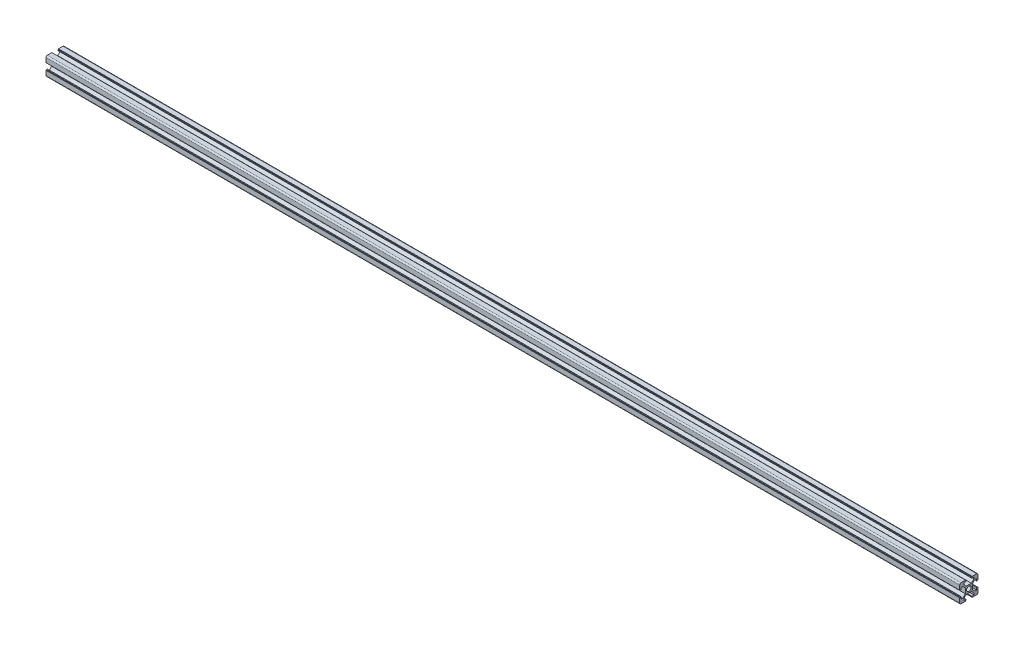
SolidWorks part; units mm, degrees
ref_plane "前视基准面" through (0, 0, 0) normal (0, 0, 1) x (1, 0, 0)
ref_plane "上视基准面" through (0, 0, 0) normal (0, 1, 0) x (1, 0, 0)
ref_plane "右视基准面" through (0, 0, 0) normal (1, 0, 0) x (0, 0, -1)
sketch "草图1" plane through (0, 0, 0) normal (0, 1, 0) x (1, 0, 0)
  line L0 (0, 0) -> (1000, 0)
  dimension "D1" = 1000
other "铝型材 20 X 20 X R1.5(1)"
ref_plane "基准面1" through (0, 0, 0) normal (1, 0, 0) x (0, 0, -1)
sketch "Sketch1" plane through (0, 0, 0) normal (1, 0, 0) x (0, 0, -1)
  line L0 (-3.6, 10) -> (-3.6, 9.5)
  line L1 (-3.6, 9.5) -> (-3.1, 9.5)
  line L2 (-3.1, 9.5) -> (-3.1, 8.5)
  line L3 (-3.1, 8.5) -> (-5.5, 8.5)
  line L4 (-8.5, -10) -> (-3.6, -10)
  line L5 (-10, -8.5) -> (-10, -3.6)
  line L6 (8.5, 10) -> (3.6, 10)
  line L7 (10, 8.5) -> (10, 3.6)
  line L8 (0, 14.8756) -> (0, 0) construction
  line L9 (0, 0) -> (14.1675, 0) construction
  line L10 (-5.5, 8.5) -> (-5.5, 6.65)
  line L11 (-5.5, 6.65) -> (-2.75, 3.9)
  line L12 (-2.75, 3.9) -> (2.75, 3.9)
  line L13 (5.5, 6.65) -> (2.75, 3.9)
  line L14 (5.5, 8.5) -> (5.5, 6.65)
  line L15 (3.1, 8.5) -> (5.5, 8.5)
  line L16 (3.1, 9.5) -> (3.1, 8.5)
  line L17 (3.6, 9.5) -> (3.1, 9.5)
  line L18 (3.6, 10) -> (3.6, 9.5)
  line L19 (-3.6, 10) -> (-8.5, 10)
  line L20 (10, 3.6) -> (9.5, 3.6)
  line L21 (9.5, 3.6) -> (9.5, 3.1)
  line L22 (9.5, 3.1) -> (8.5, 3.1)
  line L23 (8.5, 3.1) -> (8.5, 5.5)
  line L24 (8.5, 5.5) -> (6.65, 5.5)
  line L25 (6.65, 5.5) -> (3.9, 2.75)
  line L26 (3.9, 2.75) -> (3.9, -2.75)
  line L27 (6.65, -5.5) -> (3.9, -2.75)
  line L28 (8.5, -5.5) -> (6.65, -5.5)
  line L29 (8.5, -3.1) -> (8.5, -5.5)
  line L30 (9.5, -3.1) -> (8.5, -3.1)
  line L31 (9.5, -3.6) -> (9.5, -3.1)
  line L32 (10, -3.6) -> (9.5, -3.6)
  line L33 (3.6, -10) -> (3.6, -9.5)
  line L34 (3.6, -9.5) -> (3.1, -9.5)
  line L35 (3.1, -9.5) -> (3.1, -8.5)
  line L36 (3.1, -8.5) -> (5.5, -8.5)
  line L37 (5.5, -8.5) -> (5.5, -6.65)
  line L38 (5.5, -6.65) -> (2.75, -3.9)
  line L39 (2.75, -3.9) -> (-2.75, -3.9)
  line L40 (-5.5, -6.65) -> (-2.75, -3.9)
  line L41 (-5.5, -8.5) -> (-5.5, -6.65)
  line L42 (-3.1, -8.5) -> (-5.5, -8.5)
  line L43 (-3.1, -9.5) -> (-3.1, -8.5)
  line L44 (-3.6, -9.5) -> (-3.1, -9.5)
  line L45 (-3.6, -10) -> (-3.6, -9.5)
  line L46 (-10, -3.6) -> (-9.5, -3.6)
  line L47 (-9.5, -3.6) -> (-9.5, -3.1)
  line L48 (-9.5, -3.1) -> (-8.5, -3.1)
  line L49 (-8.5, -3.1) -> (-8.5, -5.5)
  line L50 (-8.5, -5.5) -> (-6.65, -5.5)
  line L51 (-6.65, -5.5) -> (-3.9, -2.75)
  line L52 (-3.9, -2.75) -> (-3.9, 2.75)
  line L53 (-6.65, 5.5) -> (-3.9, 2.75)
  line L54 (-8.5, 5.5) -> (-6.65, 5.5)
  line L55 (-8.5, 3.1) -> (-8.5, 5.5)
  line L56 (-9.5, 3.1) -> (-8.5, 3.1)
  line L57 (-9.5, 3.6) -> (-9.5, 3.1)
  line L58 (-10, 3.6) -> (-9.5, 3.6)
  line L59 (3.6, -10) -> (8.5, -10)
  line L60 (-10, 3.6) -> (-10, 8.5)
  line L61 (10, -3.6) -> (10, -8.5)
  circle A0 centre (0, 0) radius 2.5
  arc A1 (-10, 8.5) -> (-8.5, 10) centre (-8.5, 8.5) cw
  arc A2 (10, 8.5) -> (8.5, 10) centre (8.5, 8.5) ccw
  arc A3 (-8.5, -10) -> (-10, -8.5) centre (-8.5, -8.5) cw
  arc A4 (8.5, -10) -> (10, -8.5) centre (8.5, -8.5) ccw
  point P0 (-10, 0)
  point P1 (10, 0)
  point P2 (0, 10)
  point P3 (0, -10)
  point P4 (0, 0)
  point P5 (-10, -10)
  point P6 (10, -10)
  point P7 (10, 10)
  point P8 (-10, 10)
  point P13 (0, 0)
  point P36 (-10, 10)
  point P39 (10, 10)
  dimension "D1" = 11
  dimension "D2" = 20
  dimension "D3" = 6.2
  dimension "D4" = 7.2
  dimension "D5" = 6.1
  dimension "D6" = 5
  dimension "D7" = 1.5
  dimension "D8" = 45
  dimension "D9" = 0.5
  dimension "D10" = 1
  dimension "D11" = 5.5
